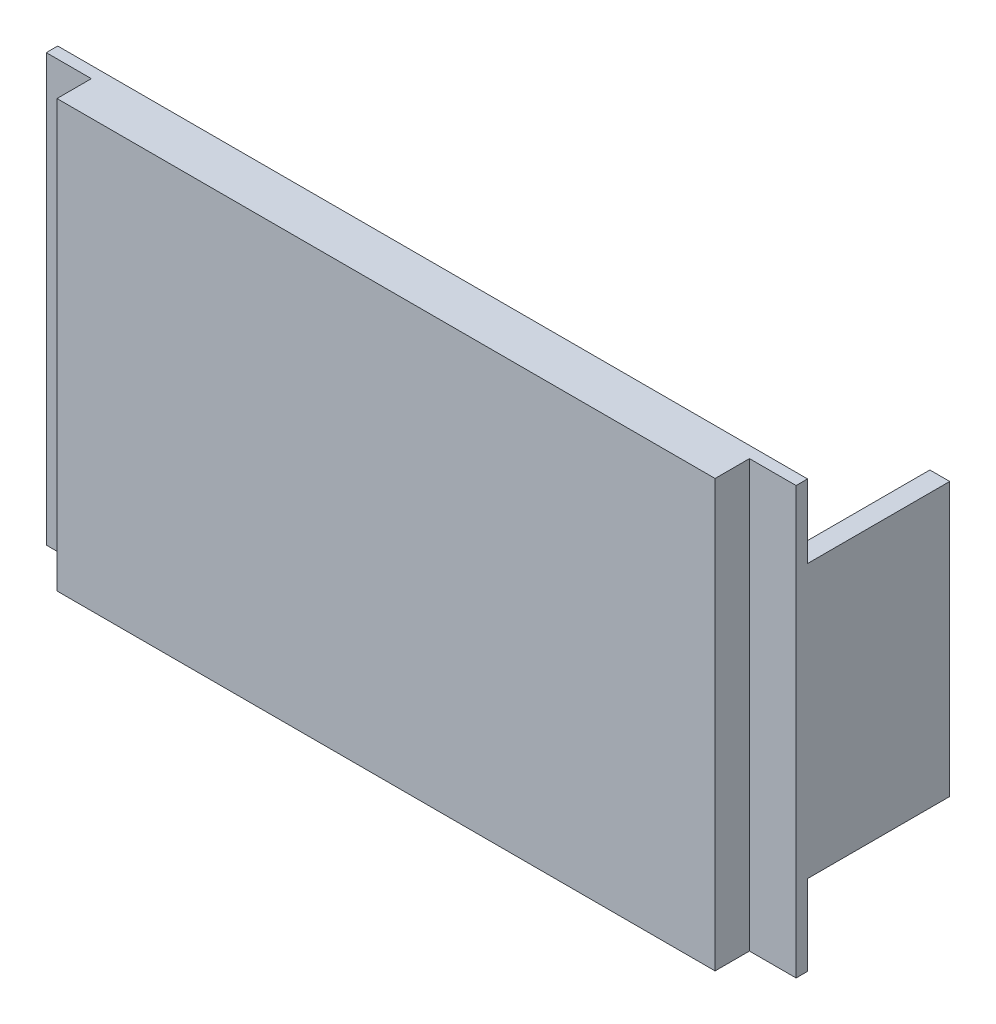
SolidWorks part; units mm, degrees
ref_plane "Front Plane" through (0, 0, 0) normal (0, 0, 1) x (1, 0, 0)
ref_plane "Top Plane" through (0, 0, 0) normal (0, 1, 0) x (1, 0, 0)
ref_plane "Right Plane" through (0, 0, 0) normal (1, 0, 0) x (0, 0, -1)
sketch "Sketch1" plane through (0, 0, 0) normal (0, 0, 1) x (1, 0, 0)
  line L1 (-49.05, -29.461) -> (49.05, -29.461)
  line L2 (-49.05, -29.461) -> (-49.05, 26.339)
  line L3 (-49.05, 26.339) -> (49.05, 26.339)
  line L4 (49.05, -29.461) -> (49.05, 26.339)
  line L5 (-49.05, -29.461) -> (49.05, 26.339) construction
  line L6 (-49.05, 26.339) -> (49.05, -29.461) construction
  point P0 (0, -1.561)
  dimension "D1" = 98.1
  dimension "D2" = 55.8
extrude "Boss-Extrude1" add sketch "Sketch1" along normal blind 6
sketch "Sketch2" plane through (0, 0, 6) normal (0, 0, 1) x (1, 0, 0)
  line L0 (-49.05, -29.461) -> (49.05, -29.461) construction
  line L1 (-49.05, 26.339) -> (-43.15, 26.339)
  line L2 (-49.05, 26.339) -> (-49.05, -29.461)
  line L3 (-49.05, -29.461) -> (-43.15, -29.461)
  line L4 (-43.15, 26.339) -> (-43.15, -29.461)
  line L6 (49.05, 26.339) -> (42.95, 26.339)
  line L7 (49.05, 26.339) -> (49.05, -29.461)
  line L8 (49.05, -29.461) -> (42.95, -29.461)
  line L9 (42.95, 26.339) -> (42.95, -29.461)
  dimension "D1" = 5.9
  dimension "D2" = 6.1
extrude "Cut-Extrude1" cut sketch "Sketch2" against normal blind 4.5
sketch "Sketch3" plane through (0, 0, 6) normal (0, 0, 1) x (1, 0, 0)
  line L9 (-38.95, -26.7938) -> (35.35, -26.7938)
  line L10 (-38.95, -26.7938) -> (-38.95, 23.239)
  line L11 (-38.95, 23.239) -> (35.35, 23.239)
  line L12 (35.35, -26.7938) -> (35.35, 23.239)
  line L17 (5.5221, -13.6723) -> (-9.2779, -13.6723)
  line L18 (5.5221, -13.6723) -> (5.5221, -28.3723)
  line L19 (5.5221, -28.3723) -> (-9.2779, -28.3723)
  line L20 (-9.2779, -13.6723) -> (-9.2779, -28.3723)
  dimension "D4" = 14.8
  dimension "D5" = 14.7
extrude "Boss-Extrude4" add sketch "Sketch3" against normal offset from surface (4.1 mm away) 1.9 contours L17 L20 L19 L18 up to face at (0, -1.561, 0)
sketch "Sketch4" plane through (0, 0, 0) normal (0, 0, -1) x (-1, 0, 0)
  line L4 (-49.05, 16.7512) -> (-46.45, 16.7512)
  line L5 (-49.05, 16.7512) -> (-49.05, -18.9488)
  line L6 (-49.05, -18.9488) -> (-46.45, -18.9488)
  line L7 (-46.45, 16.7512) -> (-46.45, -18.9488)
  line M6 (-49.05, 26.339) -> (-49.05, -29.461)
  dimension "D2" = 35.7
  dimension "D3" = 2.6
extrude "Boss-Extrude5" add sketch "Sketch4" along normal blind 18.6 contours L7 L4 L6 M6
sketch "Sketch5" plane through (0, 0, 0) normal (0, 0, -1) x (-1, 0, 0)
  line L5 (-4.85, -13.161) -> (9.95, -13.161)
  line L6 (-4.85, -13.161) -> (-4.85, -27.861)
  line L7 (-4.85, -27.861) -> (9.95, -27.861)
  line L8 (9.95, -13.161) -> (9.95, -27.861)
  dimension "D3" = 14.8
  dimension "D4" = 14.7
extrude "Boss-Extrude6" add sketch "Sketch5" along normal blind 2.2
